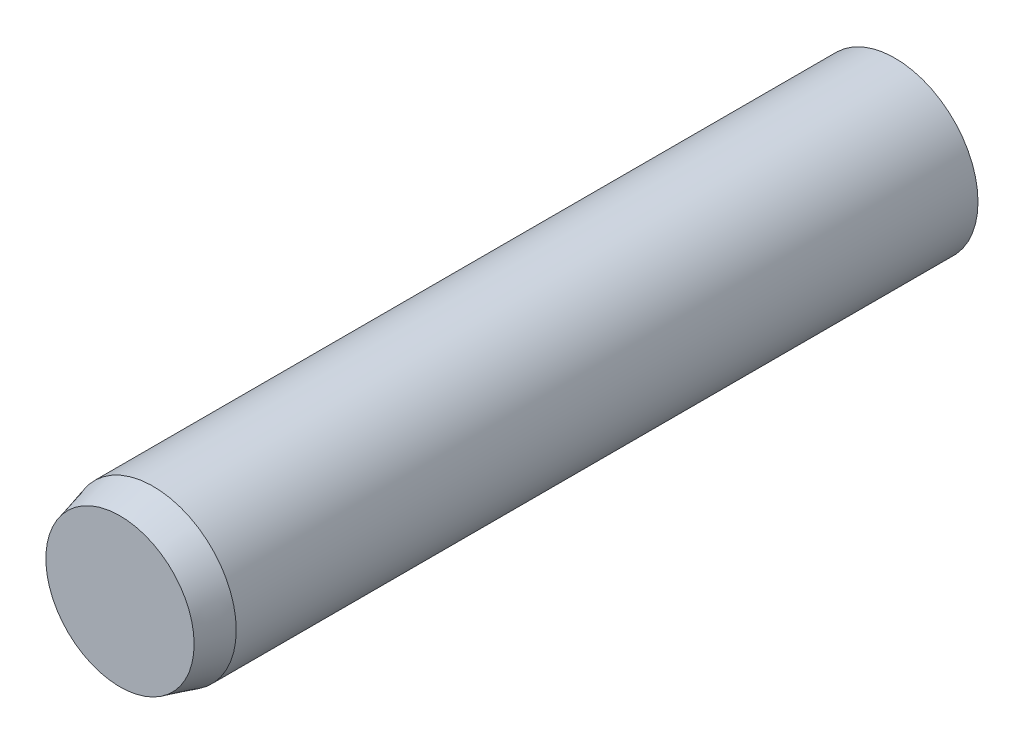
SolidWorks part; units mm, degrees
ref_plane "Ebene vorne" through (0, 0, 0) normal (0, 0, 1) x (1, 0, 0)
ref_plane "Ebene oben" through (0, 0, 0) normal (0, 1, 0) x (1, 0, 0)
ref_plane "Ebene rechts" through (0, 0, 0) normal (1, 0, 0) x (0, 0, -1)
sketch "Skizze1" plane through (0, 0, 0) normal (0, 0, 1) x (1, 0, 0)
  circle A0 centre (0, 0) radius 1.5
  dimension "D1" = 3
extrude "Aufsatz-Linear austragen1" add sketch "Skizze1" along normal blind 14
chamfer "Fase1" distance 0.6 angle 15 1 edges at (1.5, 0, 14)
